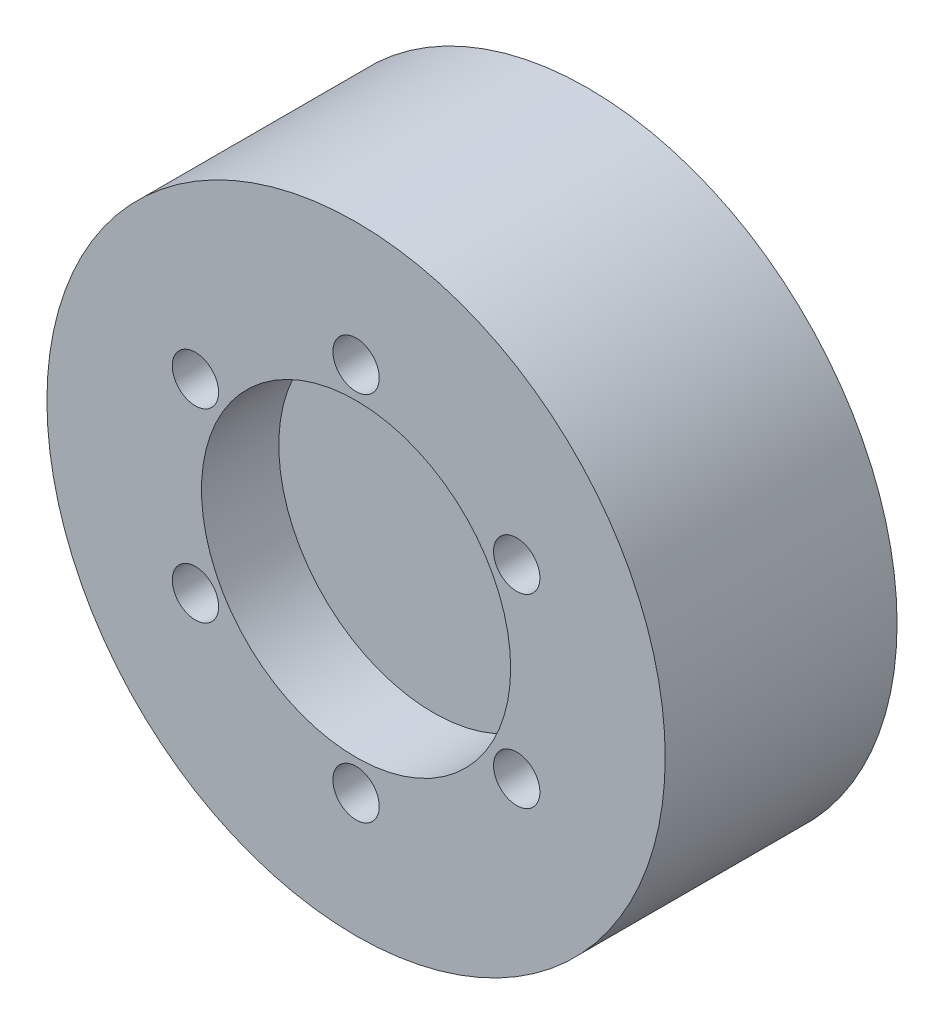
SolidWorks part; units mm, degrees
ref_plane "Front Plane" through (0, 0, 0) normal (0, 0, 1) x (1, 0, 0)
ref_plane "Top Plane" through (0, 0, 0) normal (0, 1, 0) x (1, 0, 0)
ref_plane "Right Plane" through (0, 0, 0) normal (1, 0, 0) x (0, 0, -1)
sketch "Sketch1" plane through (0, 0, 0) normal (0, 0, 1) x (1, 0, 0)
  circle A0 centre (0, 0) radius 20
  dimension "D1" = 40
extrude "Boss-Extrude1" add sketch "Sketch1" along normal blind 15
sketch "Sketch2" plane through (0, 0, 15) normal (0, 0, 1) x (1, 0, 0)
  circle A0 centre (0, 0) radius 10
  dimension "D1" = 20
extrude "Cut-Extrude1" cut sketch "Sketch2" against normal blind 5
sketch "Sketch7" plane through (0, 0, 0) normal (0, 0, -1) x (-1, 0, 0)
  circle A0 centre (0, 0) radius 17.5
  dimension "D1" = 35
extrude "Cut-Extrude2" cut sketch "Sketch7" against normal blind 3
sketch "Sketch8" plane through (0, 0, 15) normal (0, 0, 1) x (1, 0, 0)
  circle A0 centre (0, 12) radius 1.5
  circle A1 centre (10.3923, 6) radius 1.5
  circle A2 centre (10.3923, -6) radius 1.5
  circle A3 centre (0, -12) radius 1.5
  circle A4 centre (-10.3923, -6) radius 1.5
  circle A5 centre (-10.3923, 6) radius 1.5
  point P16 (0, 0)
  dimension "D1" = 3
  dimension "D2" = 12
  dimension "D3" = 6
extrude "Cut-Extrude3" cut sketch "Sketch8" against normal blind 5
